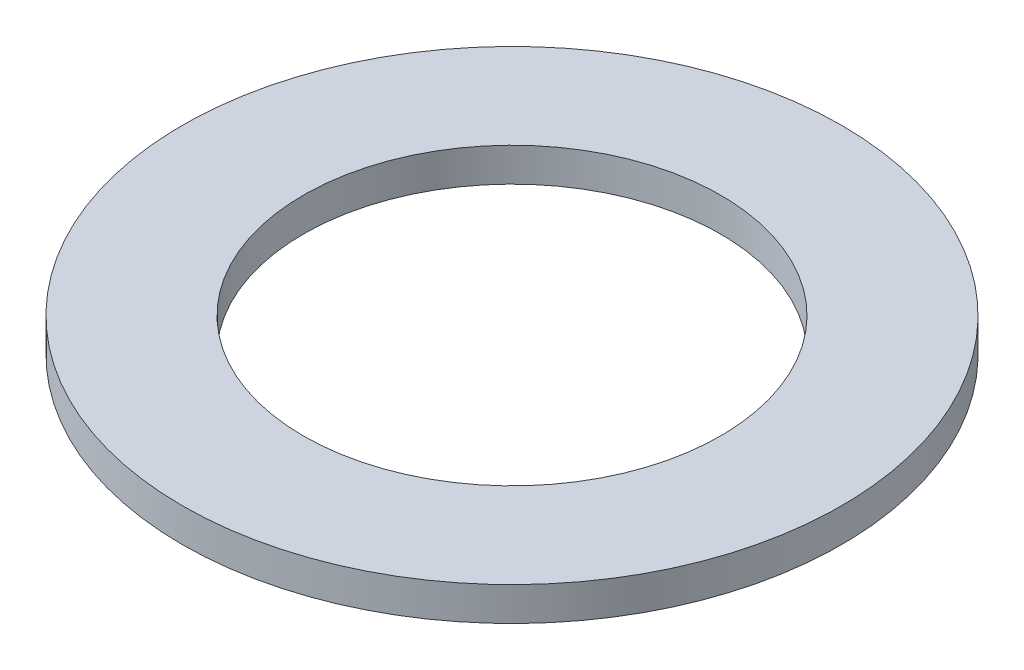
SolidWorks part; units mm, degrees
ref_plane "Front Plane" through (0, 0, 0) normal (0, 0, 1) x (1, 0, 0)
ref_plane "Top Plane" through (0, 0, 0) normal (0, 1, 0) x (1, 0, 0)
ref_plane "Right Plane" through (0, 0, 0) normal (1, 0, 0) x (0, 0, -1)
sketch "Sketch1" plane through (0, 0, 0) normal (0, 1, 0) x (1, 0, 0)
  circle A0 centre (0, 0) radius 78.2
  circle A1 centre (0, 0) radius 49.5
  dimension "D1" = 156.4
  dimension "D2" = 99
extrude "Boss-Extrude1" add sketch "Sketch1" along normal blind 8
